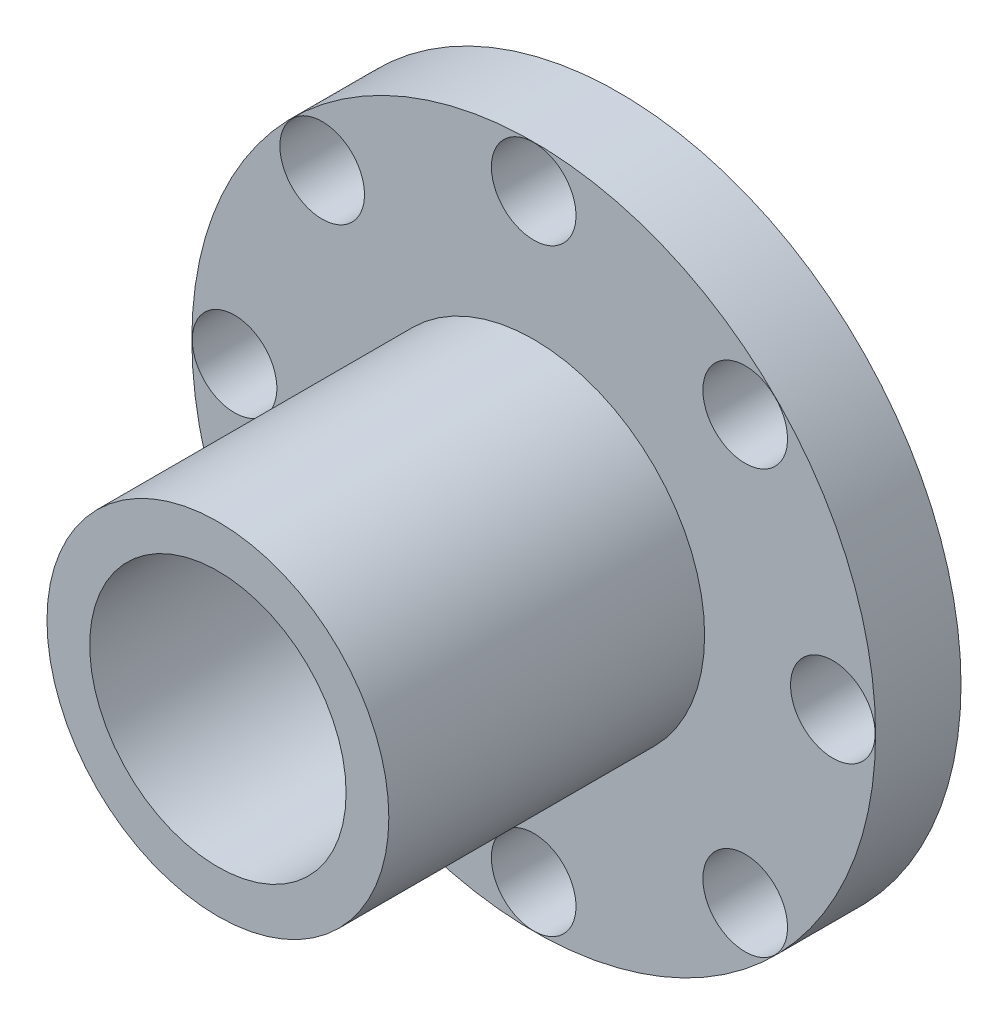
SolidWorks part; units mm, degrees
ref_plane "Front" through (0, 0, 0) normal (0, 0, 1) x (1, 0, 0)
ref_plane "Top" through (0, 0, 0) normal (0, 1, 0) x (1, 0, 0)
ref_plane "Right" through (0, 0, 0) normal (1, 0, 0) x (0, 0, -1)
sketch "草图1" plane through (0, 0, 0) normal (0, 0, 1) x (1, 0, 0)
  circle A0 centre (0, 0) radius 4
extrude "凸台-拉伸1" add sketch "草图1" along normal blind 9.39
sketch "草图2" plane through (0, 0, 9.39) normal (0, 0, 1) x (1, 0, 0)
  circle A0 centre (0, 0) radius 3
extrude "切除-拉伸1" cut sketch "草图2" against normal blind 8
sketch "草图3" plane through (0, 0, 0) normal (0, 0, -1) x (-1, 0, 0)
  circle A0 centre (0, 0) radius 3
extrude "切除-拉伸3" cut sketch "草图3" against normal blind 8
sketch "草图4" plane through (0, 0, 0) normal (0, 0, -1) x (-1, 0, 0)
  circle A0 centre (0, 0) radius 4
  circle A1 centre (0, 0) radius 8
extrude "凸台-拉伸4" add sketch "草图4" against normal blind 2 contours A1 | A0
sketch "草图5" plane through (0, 0, 0) normal (0, 0, -1) x (-1, 0, 0)
  circle A0 centre (0, 0) radius 7 construction
  circle A1 centre (7, 0) radius 0.99
  circle A2 centre (4.9497, -4.9497) radius 0.99
  circle A3 centre (0, -7) radius 0.99
  circle A4 centre (-4.9497, -4.9497) radius 0.99
  circle A5 centre (-7, 0) radius 0.99
  circle A6 centre (-4.9497, 4.9497) radius 0.99
  circle A7 centre (0, 7) radius 0.99
  circle A8 centre (4.9497, 4.9497) radius 0.99
  point P21 (0, 0)
  dimension "D1" = 1.98
  dimension "D2" = 8
extrude "切除-拉伸6" cut sketch "草图5" against normal blind 2
